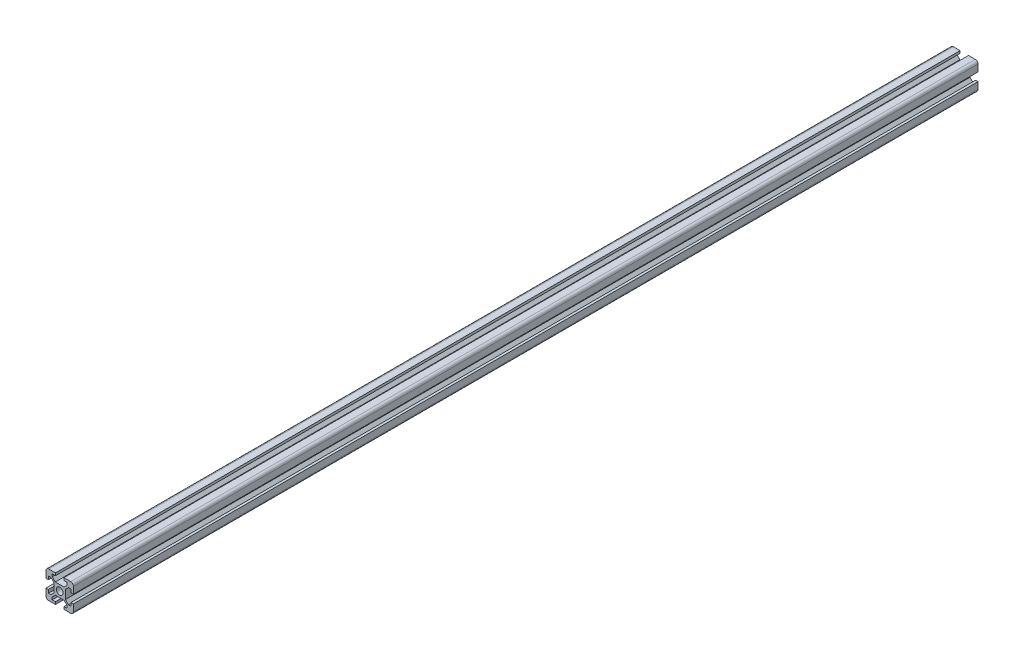
SolidWorks part; units mm, degrees
material "1060 Alloy"
ref_plane "Front Plane" through (0, 0, 0) normal (0, 0, 1) x (1, 0, 0)
ref_plane "Top Plane" through (0, 0, 0) normal (0, 1, 0) x (1, 0, 0)
ref_plane "Right Plane" through (0, 0, 0) normal (1, 0, 0) x (0, 0, -1)
sketch "Sketch1" plane through (0, 0, 0) normal (0, 0, 1) x (1, 0, 0)
  line L0 (-5.46, -6.42) -> (-3.215, -4.175)
  line L1 (-10, -10) -> (-3.06, -10)
  line L2 (-10, -10) -> (-10, -3.06)
  line L3 (-10, 10) -> (-3.06, 10)
  line L4 (10, -10) -> (10, -3.06)
  line L5 (-10, -10) -> (10, 10) construction
  line L6 (-10, 10) -> (10, -10) construction
  line L7 (-3.215, -4.175) -> (3.215, -4.175)
  line L8 (-4.175, -3.215) -> (-4.175, 3.215)
  line L9 (-3.215, 4.175) -> (3.215, 4.175)
  line L10 (4.175, -3.215) -> (4.175, 3.215)
  line L11 (-4.175, -4.175) -> (4.175, 4.175) construction
  line L12 (-4.175, 4.175) -> (4.175, -4.175) construction
  line L13 (-5.46, 6.42) -> (-5.46, 8.22)
  line L14 (-5.46, 8.22) -> (-3.06, 8.22)
  line L15 (-3.06, 8.22) -> (-3.06, 10)
  line L16 (-6.42, -5.46) -> (-4.175, -3.215)
  line L17 (5.46, 6.42) -> (5.46, 8.22)
  line L18 (5.46, 8.22) -> (3.06, 8.22)
  line L19 (3.06, 8.22) -> (3.06, 10)
  line L20 (-5.46, 6.42) -> (-3.215, 4.175)
  line L21 (6.42, 5.46) -> (8.22, 5.46)
  line L22 (8.22, 5.46) -> (8.22, 3.06)
  line L23 (8.22, 3.06) -> (10, 3.06)
  line L24 (8.22, -5.46) -> (6.42, -5.46)
  line L25 (-6.42, 5.46) -> (-4.175, 3.215)
  line L26 (8.22, -5.46) -> (8.22, -3.06)
  line L27 (8.22, -3.06) -> (10, -3.06)
  line L28 (5.46, 6.42) -> (3.215, 4.175)
  line L29 (5.46, -6.42) -> (5.46, -8.22)
  line L30 (5.46, -8.22) -> (3.06, -8.22)
  line L31 (3.06, -8.22) -> (3.06, -10)
  line L32 (6.42, 5.46) -> (4.175, 3.215)
  line L33 (-6.42, 5.46) -> (-8.22, 5.46)
  line L34 (-8.22, 5.46) -> (-8.22, 3.06)
  line L35 (-8.22, 3.06) -> (-10, 3.06)
  line L36 (6.42, -5.46) -> (4.175, -3.215)
  line L37 (-6.42, -5.46) -> (-8.22, -5.46)
  line L38 (-8.22, -5.46) -> (-8.22, -3.06)
  line L39 (-8.22, -3.06) -> (-10, -3.06)
  line L40 (5.46, -6.42) -> (3.215, -4.175)
  line L41 (-5.46, -6.42) -> (-5.46, -8.22)
  line L42 (-5.46, -8.22) -> (-3.06, -8.22)
  line L43 (-3.06, -8.22) -> (-3.06, -10)
  line L44 (-10, 3.06) -> (-10, 10)
  line L45 (3.06, 10) -> (10, 10)
  line L46 (10, 3.06) -> (10, 10)
  line L47 (3.06, -10) -> (10, -10)
  circle A0 centre (0, 0) radius 2.5
  point P0 (0, 0)
  dimension "D3" = 5
  dimension "D1" = 20
  dimension "D2" = 20
  dimension "D4" = 8.35
  dimension "D5" = 8.35
  dimension "D6" = 6.94
  dimension "D7" = 1.78
  dimension "D8" = 2.4
  dimension "D9" = 1.8
extrude "Boss-Extrude1" add sketch "Sketch1" along normal blind 660
fillet "Fillet1" radius 2 4 edges at (-10, -10, 330) (10, -10, 330) (-10, 10, 330) (10, 10, 330)
